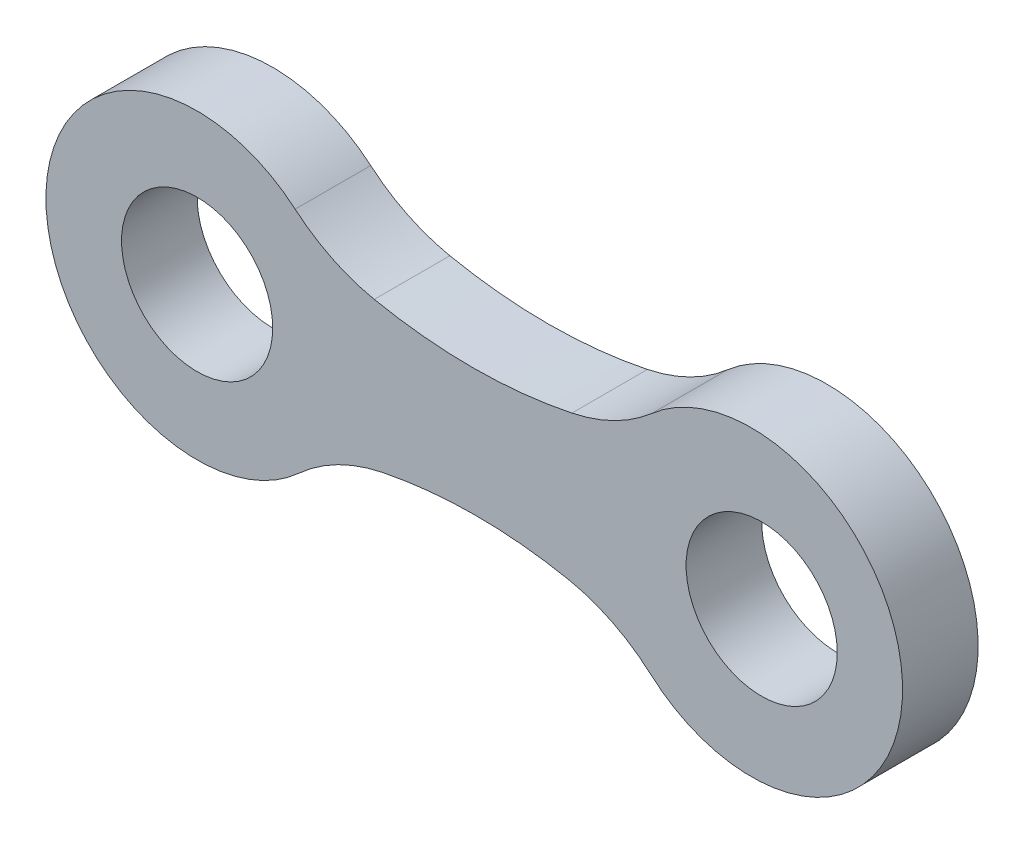
SolidWorks part; units mm, degrees
ref_plane "Front Plane" through (0, 0, 0) normal (0, 0, 1) x (1, 0, 0)
ref_plane "Top Plane" through (0, 0, 0) normal (0, 1, 0) x (1, 0, 0)
ref_plane "Right Plane" through (0, 0, 0) normal (1, 0, 0) x (0, 0, -1)
sketch "Sketch1" plane through (0, 0, 0) normal (0, 0, 1) x (1, 0, 0)
  arc A13 (-38.9931, 10.2975) -> (-38.9489, 19.2993) centre (-35.0035, 14.7789) ccw
  arc A14 (-53.1119, 19.2363) -> (-52.9617, 10.2351) centre (-57.0035, 14.6695) ccw
  arc A32 (-49.9719, 17.7057) -> (-42.1276, 17.7195) centre (-46.0832, 36.7547) ccw
  arc A33 (-49.6286, 11.9238) -> (-42.2878, 11.9358) centre (-45.928, -6.446) cw
  arc A34 (-42.2878, 11.9358) -> (-38.9931, 10.2975) centre (-43.6476, 5.0692) cw
  arc A35 (-49.6286, 11.9238) -> (-52.9617, 10.2351) centre (-48.2462, 5.0616) ccw
  arc A36 (-42.1276, 17.7195) -> (-38.9489, 19.2993) centre (-43.5518, 24.5731) ccw
  arc A37 (-49.9719, 17.7057) -> (-53.1119, 19.2363) centre (-48.5718, 24.5642) cw
extrude "Boss-Extrude1" add sketch "Sketch1" along normal blind 3
sketch "Sketch2" plane through (0, 0, 3) normal (0, 0, 1) x (1, 0, 0)
  circle A0 centre (-57.0019, 14.7046) radius 3
  circle A1 centre (-34.5955, 14.7494) radius 3
extrude "Cut-Extrude1" cut sketch "Sketch2" against normal blind 3
